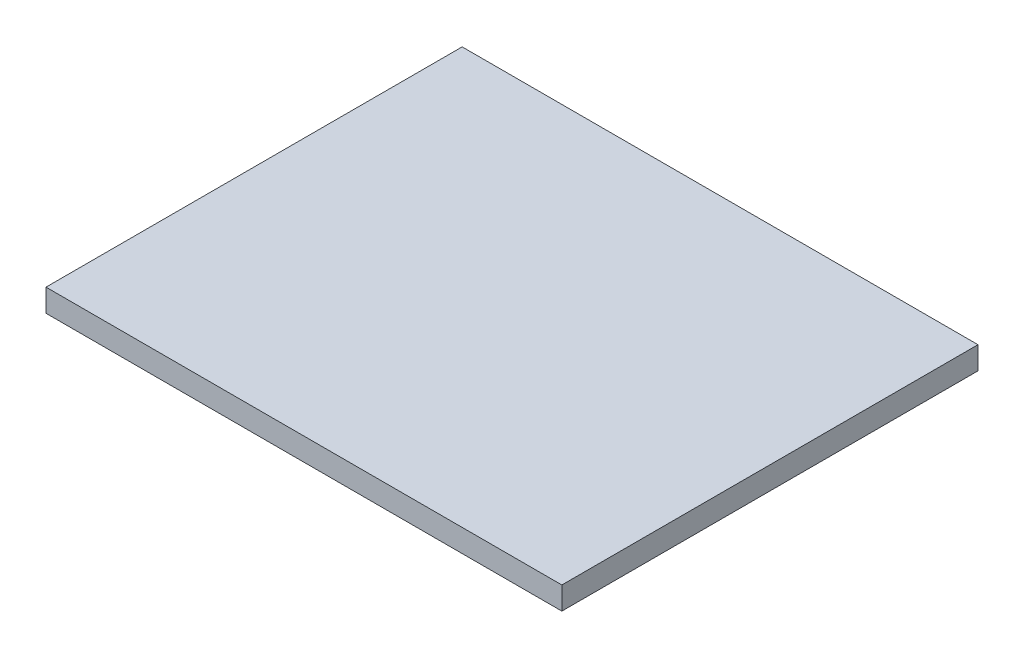
SolidWorks part; units mm, degrees
ref_plane "Front Plane" through (0, 0, 0) normal (0, 0, 1) x (1, 0, 0)
ref_plane "Top Plane" through (0, 0, 0) normal (0, 1, 0) x (1, 0, 0)
ref_plane "Right Plane" through (0, 0, 0) normal (1, 0, 0) x (0, 0, -1)
sketch "Sketch1" plane through (0, 0, 0) normal (0, 1, 0) x (1, 0, 0)
  line L1 (-8.6676, -6.9924) -> (8.6676, -6.9924)
  line L2 (-8.6676, -6.9924) -> (-8.6676, 6.9924)
  line L3 (-8.6676, 6.9924) -> (8.6676, 6.9924)
  line L4 (8.6676, -6.9924) -> (8.6676, 6.9924)
  line L5 (-8.6676, -6.9924) -> (8.6676, 6.9924) construction
  line L6 (-8.6676, 6.9924) -> (8.6676, -6.9924) construction
  point P0 (0, 0)
  point P6 (0.5683, -0.3939)
  point P7 (1.3207, -0.8105)
  point P8 (5.587, -3.569)
  point P9 (5.087, -3.5609)
extrude "Boss-Extrude1" add sketch "Sketch1" along normal blind 0.762
